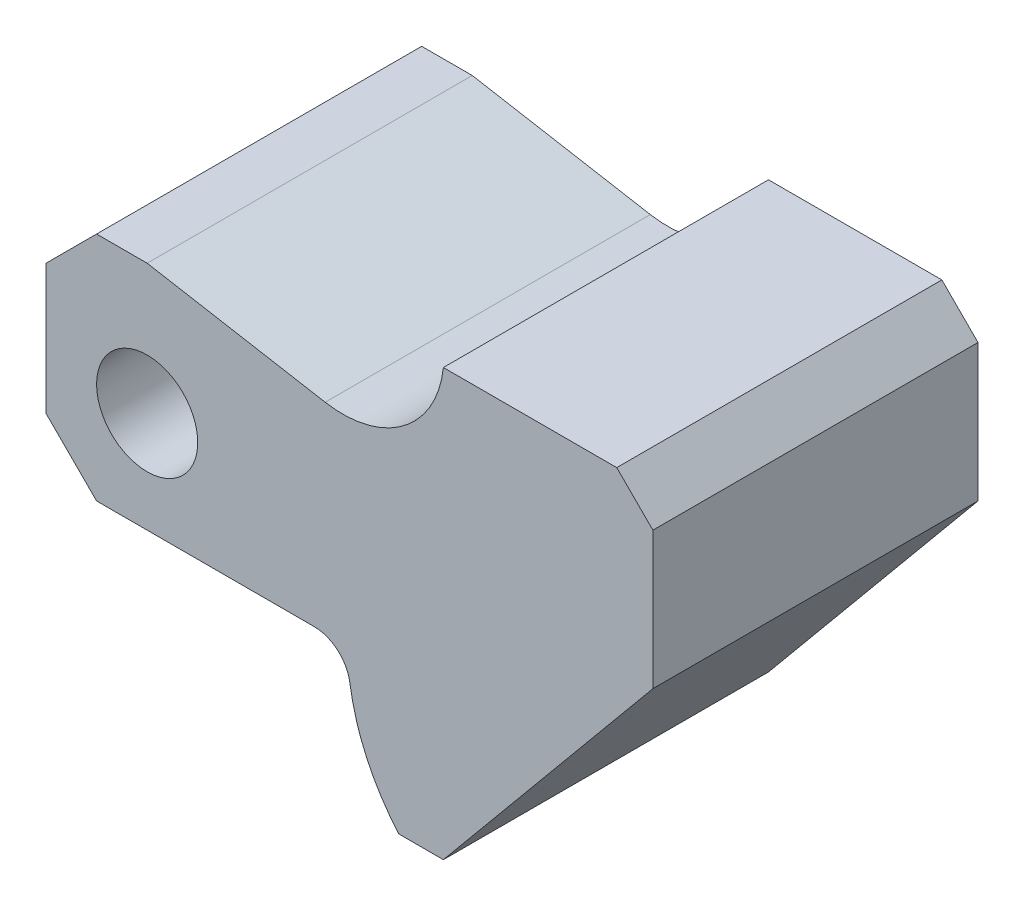
SolidWorks part; units mm, degrees
material "AISI 1020"
ref_plane "Front Plane" through (0, 0, 0) normal (0, 0, 1) x (1, 0, 0)
ref_plane "Top Plane" through (0, 0, 0) normal (0, 1, 0) x (1, 0, 0)
ref_plane "Right Plane" through (0, 0, 0) normal (1, 0, 0) x (0, 0, -1)
other "Center of Mass"
sketch "Sketch1" plane through (0, 0, 0) normal (0, 0, 1) x (1, 0, 0)
  line L0 (-79.9804, 23.3665) -> (-79.9804, 5.3665)
  line L1 (-72.9804, 30.3665) -> (-65.9804, 30.3665)
  line L2 (-72.9804, -1.6335) -> (-42.8679, -1.6335)
  line L3 (-72.9804, 30.3665) -> (-79.9804, 23.3665)
  line L8 (-79.9804, 23.3665) -> (-79.9804, 55.1551) construction
  line L9 (-79.9804, 5.3665) -> (-72.9804, -1.6335)
  line L10 (-79.9804, 5.3665) -> (-79.9804, -51.1023) construction
  line L11 (-65.9804, 30.3665) -> (-41.3371, 26.0212)
  line L12 (-65.9804, 30.3665) -> (-36.6575, 30.3665) construction
  line L13 (-24.9804, 38.3665) -> (-0.9804, 38.3665)
  line L14 (-0.9804, 38.3665) -> (4.0196, 33.3665)
  line L15 (4.0196, 33.3665) -> (4.0196, 14.3665)
  line L16 (4.0196, 14.3665) -> (-24.9804, -20.6335)
  line L17 (-31.1465, -20.6335) -> (-24.9804, -20.6335)
  circle A0 centre (-65.9804, 12.3665) radius 7
  arc A1 (-41.3371, 26.0212) -> (-24.9804, 38.3665) centre (-38.906, 39.8085) ccw
  arc A2 (-42.8679, -1.6335) -> (-37.9223, -5.8982) centre (-42.8679, -6.6335) cw
  arc A5 (-37.9223, -5.8982) -> (-31.1465, -20.6335) centre (-9.2376, -1.6335) ccw
  arc A7 (-31.1465, -20.6335) -> (-37.9223, -5.8982) centre (-9.2376, -1.6335) cw
  point P2 (-79.9804, 30.3665)
  point P3 (-79.9804, -1.6335)
  point P20 (4.0196, 38.3665)
  point P21 (0, 0)
  point P23 (0, 0)
  point P25 (-17.9587, -28.9994)
  point P27 (0, 0)
  point P28 (-33.1885, -21.6663)
  point P30 (-40.0524, -6.2613)
  dimension "D7" = 14
  dimension "D10" = 14
  dimension "D15" = 5
  dimension "D16" = 29
  dimension "D4" = 32
  dimension "D3" = 7
  dimension "D1" = 45
  dimension "D2" = 45
  dimension "D6" = 14
  dimension "D8" = 14
  dimension "D9" = 10
  dimension "D11" = 29
  dimension "D12" = 24
  dimension "D14" = 29
  dimension "D18" = 19
  dimension "D19" = 14
  dimension "D20" = 84
  dimension "D21" = 59
  dimension "D22" = 19
extrude "Boss-Extrude1" add sketch "Sketch1" along normal blind 45 contours A2 A5 L17 L16 L15 L14 L13 A1 L11 L1 L3 L0 L9 L2 A0
equation "\"A\" = 84mm"
equation "\"B\" = 59mm"
equation "\"C\"= 45mm"
